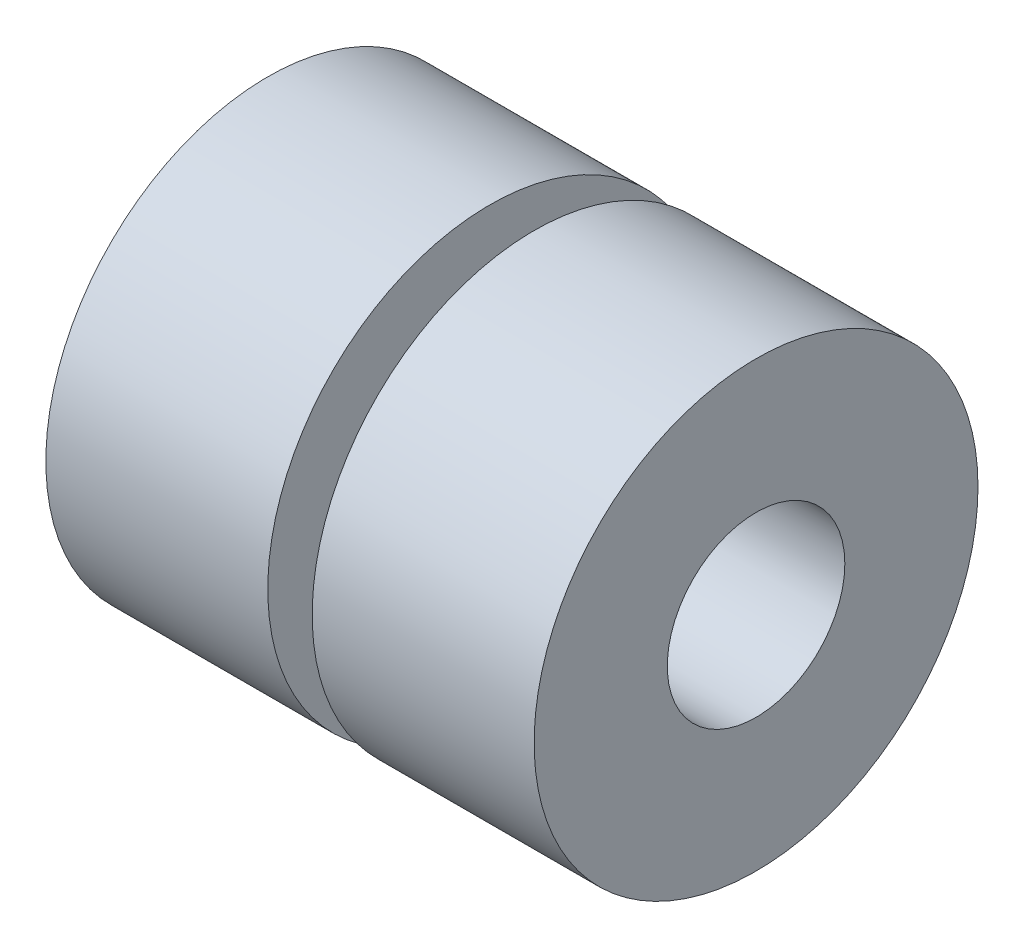
SolidWorks part; units mm, degrees
ref_plane "Спереди" through (0, 0, 0) normal (0, 0, 1) x (1, 0, 0)
ref_plane "Сверху" through (0, 0, 0) normal (0, 1, 0) x (1, 0, 0)
ref_plane "Справа" through (0, 0, 0) normal (1, 0, 0) x (0, 0, -1)
sketch "Эскиз1" plane through (0, 0, 0) normal (1, 0, 0) x (0, 0, -1)
  circle A0 centre (0, 0) radius 5
  dimension "D1" = 10
extrude "Бобышка-Вытянуть1" add sketch "Эскиз1" along normal blind 5
sketch "Эскиз2" plane through (5, 0, 0) normal (1, 0, 0) x (0, 0, -1)
  circle A0 centre (0, 0) radius 2.5
  dimension "D1" = 5
extrude "Бобышка-Вытянуть2" add sketch "Эскиз2" along normal blind 1
sketch "Эскиз3" plane through (6, 0, 0) normal (1, 0, 0) x (0, 0, -1)
  circle A0 centre (0, 0) radius 5
  dimension "D1" = 10
extrude "Бобышка-Вытянуть3" add sketch "Эскиз3" along normal blind 5
sketch "Эскиз4" plane through (11, 0, 0) normal (1, 0, 0) x (0, 0, -1)
  circle A0 centre (0, 0) radius 2
  dimension "D1" = 4
extrude "Вырез-Вытянуть1" cut sketch "Эскиз4" against normal blind 16
